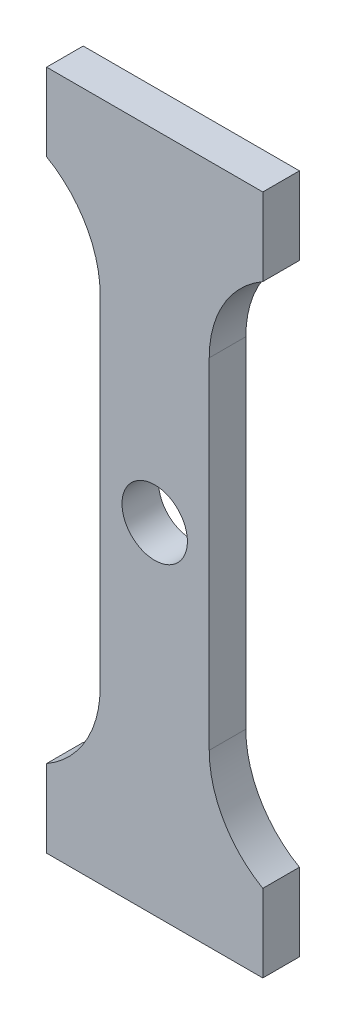
SolidWorks part; units mm, degrees
material "ASTM A36 Steel"
ref_plane "Front Plane" through (0, 0, 0) normal (0, 0, 1) x (1, 0, 0)
ref_plane "Top Plane" through (0, 0, 0) normal (0, 1, 0) x (1, 0, 0)
ref_plane "Right Plane" through (0, 0, 0) normal (1, 0, 0) x (0, 0, -1)
sketch "Sketch1" plane through (0, 0, 0) normal (0, 0, 1) x (1, 0, 0)
  line L0 (0, 0) -> (0, 50000) construction
  line L1 (0, 0) -> (50000, 0) construction
  line L2 (29.5272, 92.9707) -> (-29.5272, 92.9707)
  line L3 (-29.5272, 92.9707) -> (-29.5272, 71.7649)
  line L4 (-14.8966, 46.4189) -> (-14.8966, -46.4189)
  line L5 (14.8966, 46.4189) -> (14.8966, -46.4189)
  line L6 (29.5272, 92.9707) -> (29.5272, 71.7649)
  line L7 (29.5272, -92.9707) -> (29.5272, -71.7649)
  line L8 (-29.5272, -92.9707) -> (-29.5272, -71.7649)
  line L9 (29.5272, -92.9707) -> (-29.5272, -92.9707)
  arc A0 (-14.8966, 46.4189) -> (-29.5272, 71.7649) centre (-44.1666, 46.4189) ccw
  arc A1 (14.8966, 46.4189) -> (29.5272, 71.7649) centre (44.1666, 46.4189) cw
  arc A2 (14.8966, -46.4189) -> (29.5272, -71.7649) centre (44.1666, -46.4189) ccw
  arc A3 (-14.8966, -46.4189) -> (-29.5272, -71.7649) centre (-44.1666, -46.4189) cw
  circle A4 centre (0, 0) radius 8.9391
  point P14 (-14.8966, 0)
  point P16 (0, 92.9707)
  point P23 (14.8966, 0)
  point P24 (0, -92.9707)
extrude "Boss-Extrude1" add sketch "Sketch1" along normal blind 10
